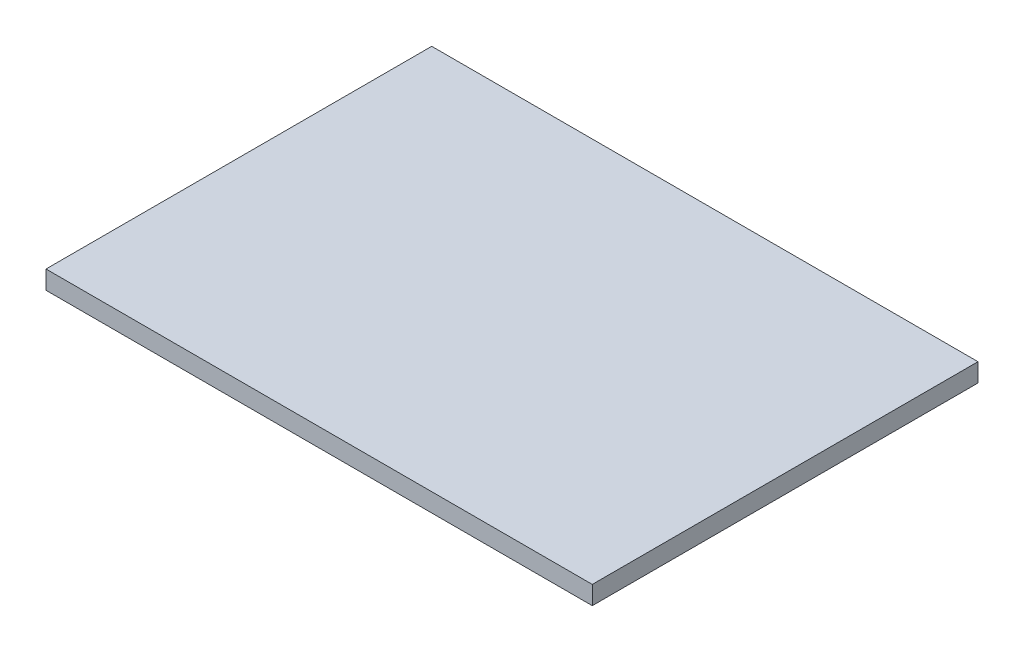
SolidWorks part; units mm, degrees
ref_plane "Front Plane" through (0, 0, 0) normal (0, 0, 1) x (1, 0, 0)
ref_plane "Top Plane" through (0, 0, 0) normal (0, 1, 0) x (1, 0, 0)
ref_plane "Right Plane" through (0, 0, 0) normal (1, 0, 0) x (0, 0, -1)
sketch "Sketch1" plane through (0, 0, 0) normal (0, 1, 0) x (1, 0, 0)
  line L1 (-148, -104.5) -> (148, -104.5)
  line L2 (-148, -104.5) -> (-148, 104.5)
  line L3 (-148, 104.5) -> (148, 104.5)
  line L4 (148, -104.5) -> (148, 104.5)
  line L5 (-148, -104.5) -> (148, 104.5) construction
  line L6 (-148, 104.5) -> (148, -104.5) construction
  point P0 (0, 0)
  dimension "D1" = 296
  dimension "D2" = 209
extrude "Extrude1" add sketch "Sketch1" along normal blind 10
